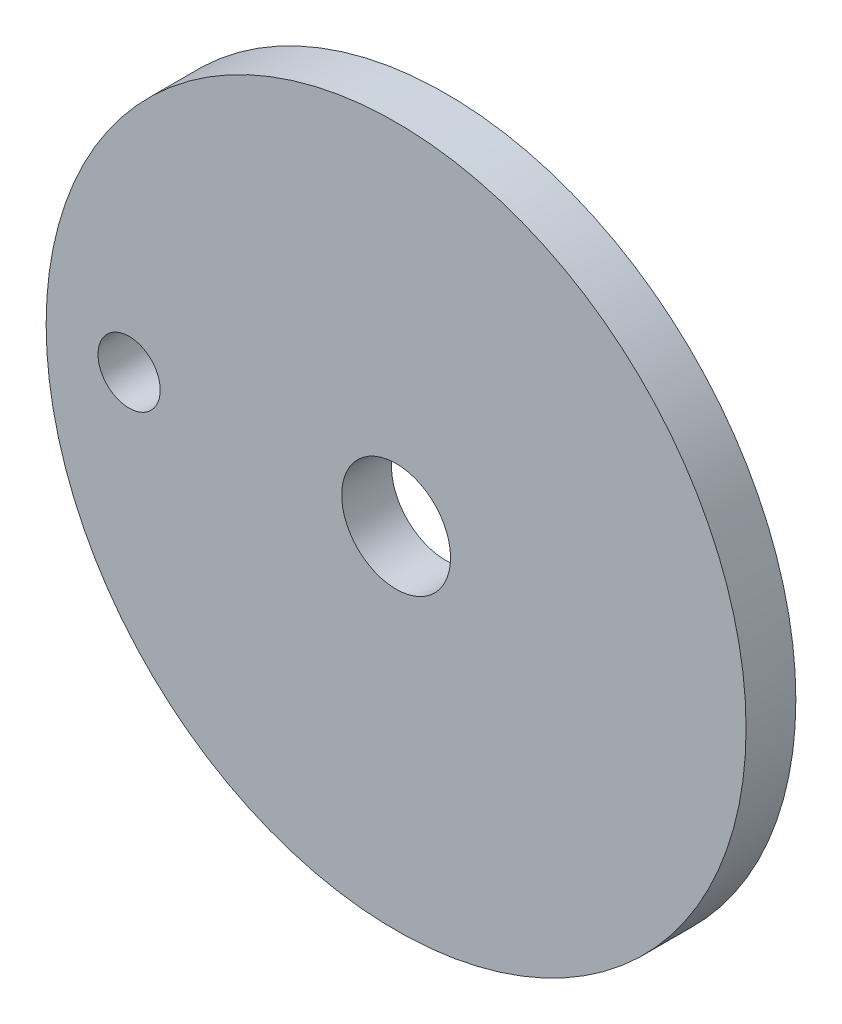
SolidWorks part; units mm, degrees
ref_plane "Спереди" through (0, 0, 0) normal (0, 0, 1) x (1, 0, 0)
ref_plane "Сверху" through (0, 0, 0) normal (0, 1, 0) x (1, 0, 0)
ref_plane "Справа" through (0, 0, 0) normal (1, 0, 0) x (0, 0, -1)
sketch "Эскиз2" plane through (0, 0, 0) normal (0, 0, 1) x (1, 0, 0)
  circle A0 centre (0, 0) radius 22.5
  circle A1 centre (0, 0) radius 3.5
extrude "Вытянуть2" add sketch "Эскиз2" along normal blind 3.2
sketch "Эскиз3" [suppressed] plane through (0, 0, 0) normal (1, 0, 0) x (0, 0, -1)
  line L0 (-1.6, 22.5) -> (-1.6, 23.5665) construction
sketch "Эскиз4" plane through (0, 0, 3.2) normal (0, 0, 1) x (1, 0, 0)
  circle A0 centre (-17.1656, 0) radius 2
extrude "Вырез-Вытянуть1" cut sketch "Эскиз4" against normal blind 15
